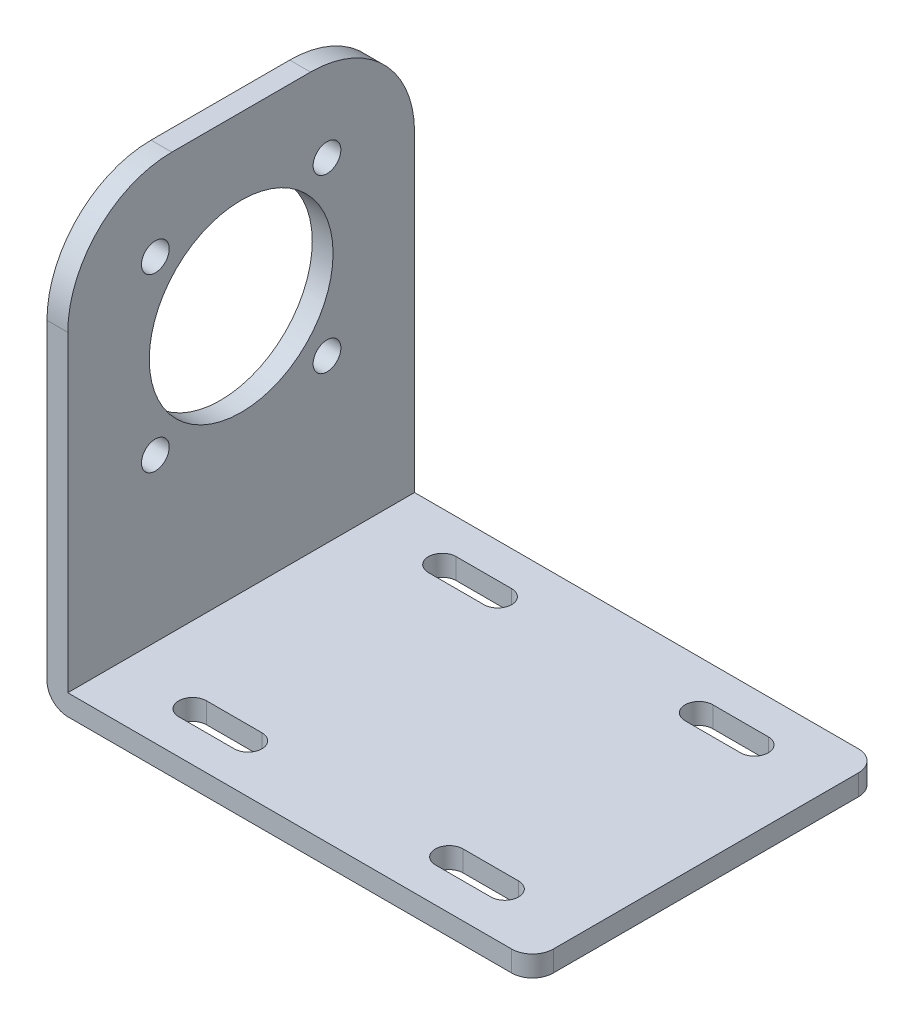
SolidWorks part; units mm, degrees
ref_plane "Front Plane" through (0, 0, 0) normal (0, 0, 1) x (1, 0, 0)
ref_plane "Top Plane" through (0, 0, 0) normal (0, 1, 0) x (1, 0, 0)
ref_plane "Right Plane" through (0, 0, 0) normal (1, 0, 0) x (0, 0, -1)
sketch "Sketch1" plane through (0, 0, 0) normal (0, 1, 0) x (1, 0, 0)
  line L0 (12, 50) -> (12, 0) construction
  line L1 (0, 0) -> (70, 0)
  line L2 (0, 0) -> (0, 50)
  line L3 (0, 50) -> (70, 50)
  line L4 (70, 0) -> (70, 50)
  line L5 (61, 50) -> (61, 0) construction
  line L6 (0, 45) -> (70, 45) construction
  line L7 (14, 43) -> (22, 43) construction
  line L8 (14, 45) -> (22, 45)
  line L9 (14, 41) -> (22, 41)
  line L10 (51, 43) -> (59, 43) construction
  line L11 (51, 45) -> (59, 45)
  line L12 (51, 41) -> (59, 41)
  line L13 (0, 25) -> (70, 25) construction
  line L14 (51, 7) -> (59, 7) construction
  line L15 (51, 5) -> (59, 5)
  line L16 (51, 9) -> (59, 9)
  line L17 (14, 7) -> (22, 7) construction
  line L18 (14, 5) -> (22, 5)
  line L19 (14, 9) -> (22, 9)
  arc A0 (14, 45) -> (14, 41) centre (14, 43) ccw
  arc A1 (22, 41) -> (22, 45) centre (22, 43) ccw
  arc A2 (51, 45) -> (51, 41) centre (51, 43) ccw
  arc A3 (59, 41) -> (59, 45) centre (59, 43) ccw
  arc A4 (51, 5) -> (51, 9) centre (51, 7) cw
  arc A5 (59, 9) -> (59, 5) centre (59, 7) cw
  arc A6 (14, 5) -> (14, 9) centre (14, 7) cw
  arc A7 (22, 9) -> (22, 5) centre (22, 7) cw
  point P13 (18, 43)
  point P20 (55, 43)
  point P29 (55, 7)
  point P36 (18, 7)
  dimension "D7" = 8
  dimension "D1" = 50
  dimension "D2" = 70
  dimension "D3" = 12
  dimension "D4" = 9
  dimension "D5" = 5
  dimension "D6" = 4
  dimension "D8" = 4
  dimension "D9" = 8
extrude "Boss-Extrude1" add sketch "Sketch1" along normal blind 3
sketch "Sketch2" plane through (0, 3, 0) normal (0, 1, 0) x (1, 0, 0)
  line L0 (0, 0) -> (70, 0) construction
  line L1 (0, 50) -> (3, 50)
  line L2 (0, 50) -> (0, 0)
  line L3 (0, 0) -> (3, 0)
  line L4 (3, 50) -> (3, 0)
  dimension "D1" = 3
extrude "Boss-Extrude2" add sketch "Sketch2" along normal blind 60
sketch "Sketch3" plane through (0, 0, 0) normal (-1, 0, 0) x (0, 0, 1)
  line L0 (-25, 63) -> (-25, 0) construction
  line L1 (-50, 63) -> (0, 63) construction
  line L2 (-50, 0) -> (0, 0) construction
  circle A0 centre (-25, 38.75) radius 13.25
  circle A1 centre (-25, 38.75) radius 17.5 construction
  circle A2 centre (-25, 56.25) radius 2
  circle A3 centre (-12.6256, 51.1244) radius 2
  circle A4 centre (-7.5, 38.75) radius 2
  circle A5 centre (-12.6256, 26.3756) radius 2
  circle A6 centre (-25, 21.25) radius 2
  circle A7 centre (-37.3744, 26.3756) radius 2
  circle A8 centre (-42.5, 38.75) radius 2
  circle A9 centre (-37.3744, 51.1244) radius 2
  point P12 (-25, 38.75)
  point P27 (-25, 38.75)
  dimension "D1" = 26.5
  dimension "D3" = 35
  dimension "D4" = 4
  dimension "D2" = 24.25
  dimension "D5" = 8
extrude "Cut-Extrude1" cut sketch "Sketch3" against normal blind 60 contours A0 | A5 | A3 | A9 | A7
fillet "Fillet1" radius 15 2 edges at (1.5, 63, -50) (1.5, 63, 0)
fillet "Fillet2" radius 3 3 edges at (0, 0, -25) (70, 1.5, 0) (70, 1.5, -50)
